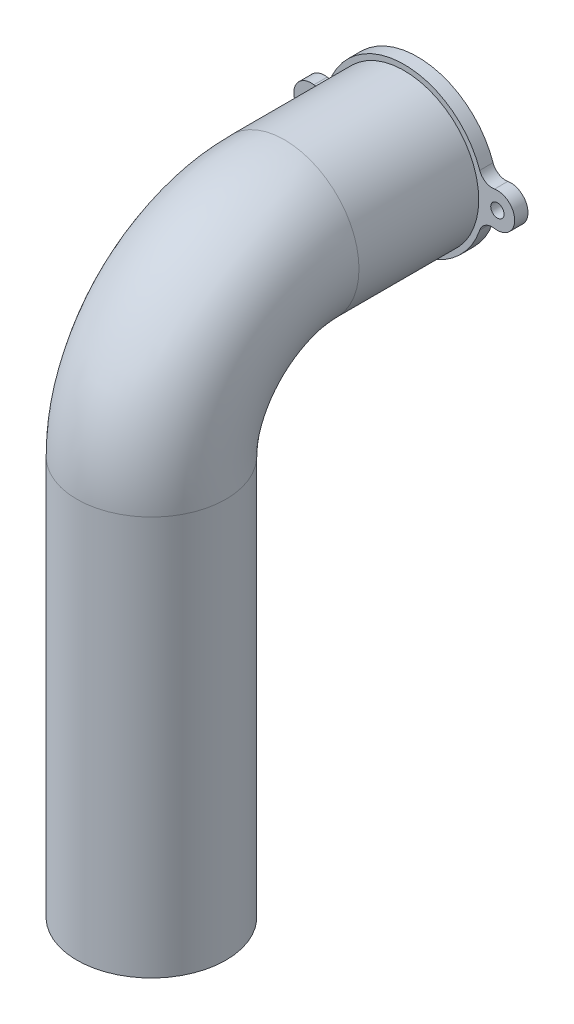
SolidWorks part; units mm, degrees
material "6063-T6"
ref_plane "Front Plane" through (0, 0, 0) normal (0, 0, 1) x (1, 0, 0)
ref_plane "Top Plane" through (0, 0, 0) normal (0, 1, 0) x (1, 0, 0)
ref_plane "Right Plane" through (0, 0, 0) normal (1, 0, 0) x (0, 0, -1)
sketch "Sketch1" plane through (0, 0, 0) normal (0, 0, 1) x (1, 0, 0)
  line L0 (-35, 0) -> (35, 0) construction
  line L1 (0, 30) -> (0, 26)
  line L2 (0, -26) -> (0, -30)
  circle A11 centre (-35, 0) radius 2.5
  arc A12 (-33.9321, 6.4117) -> (-33.9321, -6.4117) centre (-35, 0) ccw
  arc A13 (0, 30) -> (-28.3806, 9.7232) centre (0, 0) ccw
  arc A14 (0, 26) -> (0, -26) centre (0, 0) ccw
  arc A15 (-28.3806, 9.7232) -> (-33.9321, 6.4117) centre (-33.1107, 11.3437) cw
  arc A16 (-28.3806, -9.7232) -> (-33.9321, -6.4117) centre (-33.1107, -11.3437) ccw
  arc A19 (-28.3806, -9.7232) -> (0, -30) centre (0, 0) ccw
  point P2 (0, 0)
  dimension "D1" = 70
  dimension "D3" = 4
  dimension "D4" = 4
  dimension "D5" = 26
  dimension "D2" = 5
  dimension "D6" = 5
  dimension "D7" = 5
extrude "Boss-Extrude1" add sketch "Sketch1" along normal blind 5
mirror "Mirror1" about plane through (0, 30, 5) normal (-1, 0, 0) of "Boss-Extrude1"
sketch "Sketch2" plane through (0, 0, 5) normal (0, 0, 1) x (1, 0, 0)
  circle A0 centre (0, 0) radius 26
  circle A1 centre (0, 0) radius 28
  dimension "D1" = 52
  dimension "D2" = 56
sketch "Sketch3" plane through (0, 0, 0) normal (1, 0, 0) x (0, 0, -1)
  line L0 (0, 0) -> (-50, 0)
  line L1 (-100, -50) -> (-100, -200)
  arc A0 (-50, 0) -> (-100, -50) centre (-50, -50) ccw
  dimension "D2" = 50
  dimension "D3" = 150
  dimension "D1" = 50
sweep "Sweep1" add profiles "Sketch2" path "Sketch3"
